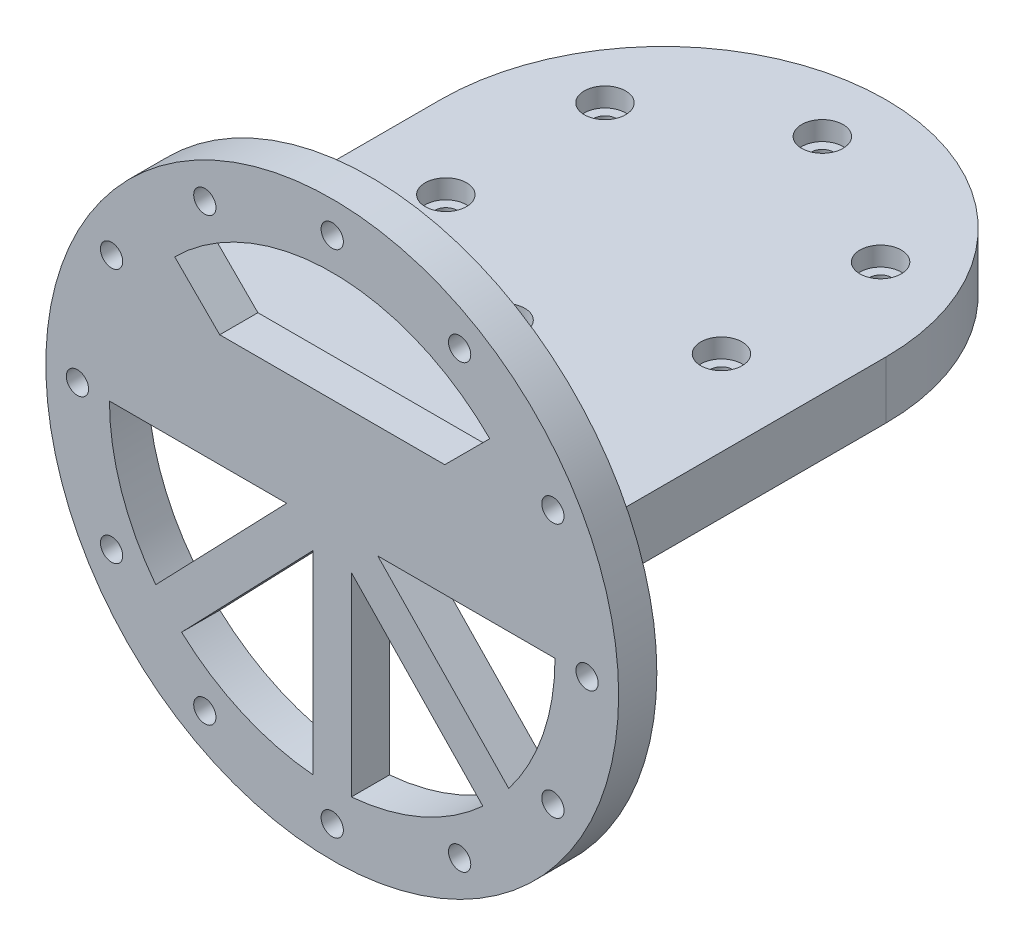
SolidWorks part; units mm, degrees
ref_plane "Front Plane" through (0, 0, 0) normal (0, 0, 1) x (1, 0, 0)
ref_plane "Top Plane" through (0, 0, 0) normal (0, 1, 0) x (1, 0, 0)
ref_plane "Right Plane" through (0, 0, 0) normal (1, 0, 0) x (0, 0, -1)
sketch "Sketch1" plane through (0, 0, 0) normal (0, 1, 0) x (1, 0, 0)
  circle A0 centre (0, 0) radius 35
  dimension "D1" = 70
extrude "Boss-Extrude1" add sketch "Sketch1" along normal blind 9
sketch "Sketch2" plane through (0, 0, 0) normal (0, -1, 0) x (1, 0, 0)
  circle A0 centre (0, 0) radius 30
  dimension "D1" = 60
extrude "Cut-Extrude1" cut sketch "Sketch2" against normal blind 3
sketch "Sketch3" plane through (0, 9, 0) normal (0, 1, 0) x (1, 0, 0)
  line L0 (0, 0) -> (0, -25) construction
  circle A0 centre (0, 0) radius 25 construction
  circle A1 centre (0, -25) radius 1.75
  circle A2 centre (-21.6506, -12.5) radius 1.75
  circle A3 centre (-21.6506, 12.5) radius 1.75
  circle A4 centre (0, 25) radius 1.75
  circle A5 centre (21.6506, 12.5) radius 1.75
  circle A6 centre (21.6506, -12.5) radius 1.75
  point P17 (0, 0)
  dimension "D1" = 50
  dimension "D2" = 3.5
  dimension "D3" = 6
extrude "Cut-Extrude2" cut sketch "Sketch3" against normal through all
sketch "Sketch4" plane through (0, 9, 0) normal (0, 1, 0) x (1, 0, 0)
  circle A0 centre (0, 25) radius 3.25
  circle A1 centre (21.6506, 12.5) radius 3.25
  circle A2 centre (21.6506, -12.5) radius 3.25
  circle A3 centre (0, -25) radius 3.25
  circle A4 centre (-21.6506, -12.5) radius 3.25
  circle A5 centre (-21.6506, 12.5) radius 3.25
  point P15 (0, 0)
  dimension "D1" = 6.5
  dimension "D2" = 6
extrude "Cut-Extrude3" cut sketch "Sketch4" against normal blind 3
sketch "Sketch5" plane through (0, 9, 0) normal (0, 1, 0) x (1, 0, 0)
  line L0 (-35, 0) -> (35, 0) construction
  line L1 (0, 0) -> (0, -35) construction
  line L2 (-35, 0) -> (-35, -52)
  line L3 (-35, -52) -> (35, -52)
  line L4 (35, -52) -> (35, 0)
  circle A0 centre (0, 0) radius 35 construction
  arc A1 (-35, 0) -> (35, 0) centre (0, 0) ccw
  dimension "D1" = 52
extrude "Boss-Extrude3" add sketch "Sketch5" against normal blind 9
sketch "Sketch21" plane through (0, 0, 0) normal (0, -1, 0) x (1, 0, 0)
  line L0 (-35, 0) -> (-35, 52) construction
  line L1 (35, 52) -> (-35, 52)
  line L2 (35, 52) -> (35, 46)
  line L3 (35, 46) -> (-35, 46)
  line L4 (-35, 52) -> (-35, 46)
  dimension "D1" = 6
extrude "Boss-Extrude8" add sketch "Sketch21" along normal blind 6
sketch "Sketch26" plane through (0, 0, 52) normal (0, 0, 1) x (1, 0, 0)
  line L0 (35, -6) -> (-35, -6) construction
  circle A0 centre (0, -6) radius 45
  dimension "D1" = 90
extrude "Boss-Extrude12" add sketch "Sketch26" against normal blind 6
sketch "Sketch27" plane through (0, 0, 52) normal (0, 0, 1) x (1, 0, 0)
  line L0 (0, -51) -> (0, 39) construction
  line L1 (45, -6) -> (-45, -6) construction
  circle A0 centre (0, -6) radius 45 construction
  circle A1 centre (0, -6) radius 40 construction
  circle A2 centre (0, -46.0317) radius 1.75
  circle A3 centre (-20.0158, -40.6685) radius 1.75
  circle A4 centre (-34.6685, -26.0158) radius 1.75
  circle A5 centre (-40.0317, -6) radius 1.75
  circle A6 centre (-34.6685, 14.0158) radius 1.75
  circle A7 centre (-20.0158, 28.6685) radius 1.75
  circle A8 centre (0, 34.0317) radius 1.75
  circle A9 centre (20.0158, 28.6685) radius 1.75
  circle A10 centre (34.6685, 14.0158) radius 1.75
  circle A11 centre (40.0317, -6) radius 1.75
  circle A12 centre (34.6685, -26.0158) radius 1.75
  circle A13 centre (20.0158, -40.6685) radius 1.75
  point P35 (0, -6)
  dimension "D1" = 80
  dimension "D2" = 3.5
  dimension "D3" = 12
extrude "Cut-Extrude20" cut sketch "Sketch27" against normal up to next
sketch "Sketch28" plane through (0, 0, 46) normal (0, 0, -1) x (-1, 0, 0)
  line L0 (45, -6) -> (0, -6) construction
  circle A1 centre (0, -46.0317) radius 3.25
  circle A2 centre (0, -6) radius 45 construction
  circle A3 centre (-20, -40.6727) radius 3.25
  circle A4 centre (-34.641, -26.0317) radius 3.25
  circle A5 centre (-40, -6.0317) radius 3.25
  circle A6 centre (-34.641, 13.9683) radius 3.25
  circle A7 centre (-20, 28.6093) radius 3.25
  circle A8 centre (0, 33.9683) radius 3.25
  circle A9 centre (20, 28.6093) radius 3.25
  circle A10 centre (34.641, 13.9683) radius 3.25
  circle A11 centre (40, -6.0317) radius 3.25
  circle A12 centre (34.641, -26.0317) radius 3.25
  circle A13 centre (20, -40.6727) radius 3.25
  point P32 (0, -6.0317)
  dimension "D1" = 6.5
extrude "Cut-Extrude21" cut sketch "Sketch28" against normal blind 3
sketch "Sketch30" plane through (0, 0, 46) normal (0, 0, -1) x (-1, 0, 0)
  line L0 (-45, -6) -> (45, -6) construction
  line L1 (0, -51) -> (0, -6) construction
  line L2 (-3, -10.325) -> (-3, -40.8712)
  line L3 (3, -10.325) -> (3, -40.8712)
  line L4 (-7.1648, -6) -> (-35, -6)
  line L5 (7.1648, -6) -> (35, -6)
  line L6 (0, -6) -> (-31.8198, 25.8198) construction
  line L7 (0, -6) -> (31.8198, 25.8198) construction
  line L8 (-24.7487, 18.7487) -> (-17.6777, 11.6777)
  line L9 (17.6777, 11.6777) -> (24.7487, 18.7487)
  line L10 (-17.6777, 11.6777) -> (17.6777, 11.6777)
  line L11 (-3, -6) -> (-25.7876, -29.6643) construction
  line L12 (-3, -10.325) -> (-23.666, -31.7861)
  line L13 (-7.1648, -6) -> (-27.7295, -27.3559)
  line L14 (7.1648, -6) -> (27.7295, -27.3559)
  line L15 (3, -10.325) -> (23.666, -31.7861)
  circle A0 centre (0, -6) radius 45 construction
  arc A1 (-35, -6) -> (-27.7295, -27.3559) centre (0, -6) ccw
  arc A2 (3, -40.8712) -> (23.666, -31.7861) centre (0, -6) ccw
  arc A3 (-24.7487, 18.7487) -> (24.7487, 18.7487) centre (0, -6) cw
  arc A4 (27.7295, -27.3559) -> (35, -6) centre (0, -6) ccw
  arc A5 (-23.666, -31.7861) -> (-3, -40.8712) centre (0, -6) ccw
  dimension "D1" = 70
  dimension "D4" = 35
  dimension "D5" = 3
  dimension "D2" = 3
  dimension "D3" = 135
  dimension "D6" = 3
extrude "Cut-Extrude23" cut sketch "Sketch30" against normal through all
